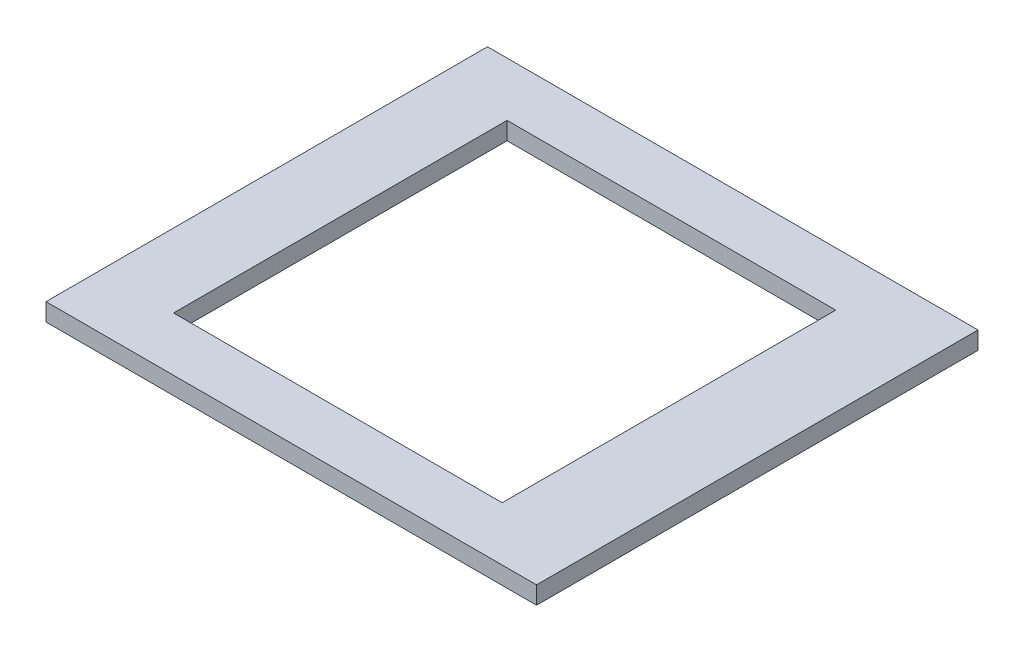
SolidWorks part; units mm, degrees
ref_plane "Front Plane" through (0, 0, 0) normal (0, 0, 1) x (1, 0, 0)
ref_plane "Top Plane" through (0, 0, 0) normal (0, 1, 0) x (1, 0, 0)
ref_plane "Right Plane" through (0, 0, 0) normal (1, 0, 0) x (0, 0, -1)
sketch "Sketch1" plane through (0, 0, 0) normal (0, 1, 0) x (1, 0, 0)
  line L1 (0, 0) -> (500, 0)
  line L2 (0, 0) -> (0, 450)
  line L3 (0, 450) -> (500, 450)
  line L4 (500, 0) -> (500, 450)
  line L5 (75, 395) -> (410, 395)
  line L6 (75, 395) -> (75, 55)
  line L7 (75, 55) -> (410, 55)
  line L8 (410, 395) -> (410, 55)
  dimension "D1" = 500
  dimension "D2" = 450
  dimension "D3" = 55
  dimension "D4" = 55
  dimension "D5" = 90
  dimension "D6" = 75
extrude "Boss-Extrude1" add sketch "Sketch1" along normal blind 18
